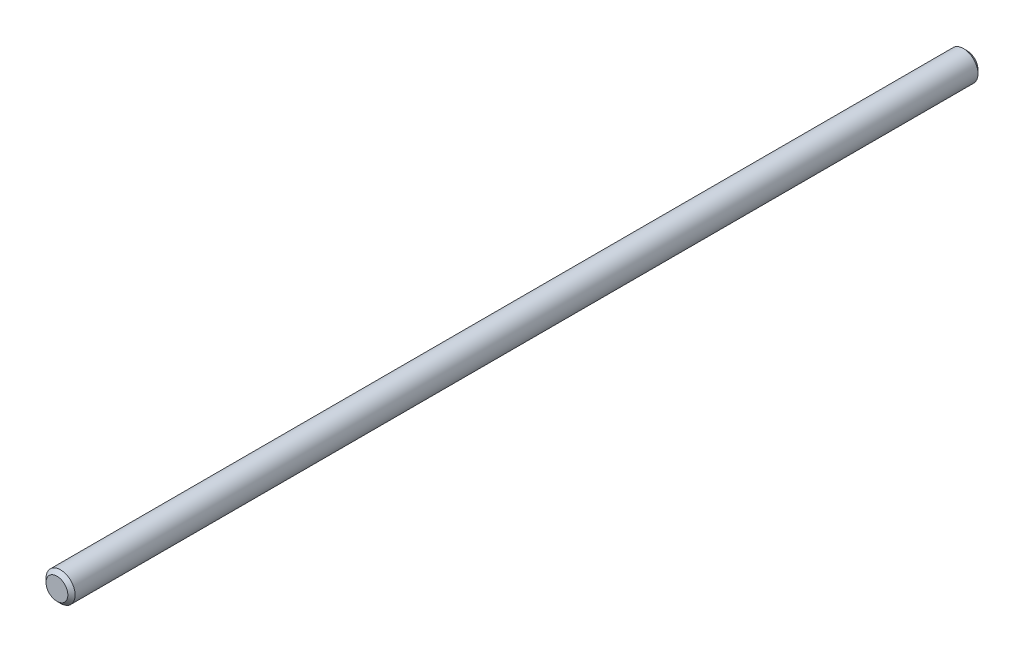
SolidWorks part; units mm, degrees
ref_plane "Front Plane" through (0, 0, 0) normal (0, 0, 1) x (1, 0, 0)
ref_plane "Top Plane" through (0, 0, 0) normal (0, 1, 0) x (1, 0, 0)
ref_plane "Right Plane" through (0, 0, 0) normal (1, 0, 0) x (0, 0, -1)
sketch "Sketch1" plane through (0, 0, 0) normal (0, 0, 1) x (1, 0, 0)
  circle A0 centre (0, 0) radius 4
  dimension "D1" = 8
extrude "Boss-Extrude1" add sketch "Sketch1" along normal blind 125
cosmetic thread "Cosmetic Thread1" parameters "D1"=30, "D2"=6.619
cosmetic thread "Cosmetic Thread3" parameters "D1"=30, "D2"=6.619
mirror "Mirror2" about plane through (0, 0, 0) normal (0, 0, 1) of bodies 101
chamfer "Chamfer2" distance 1 angle 45 1 edges at (4, 0, -125)
chamfer "Chamfer3" distance 1 angle 45 1 edges at (4, 0, 125)
ref_plane "Plane1" through (0, 0, 95) normal (0, 0, 1) x (1, 0, 0)
